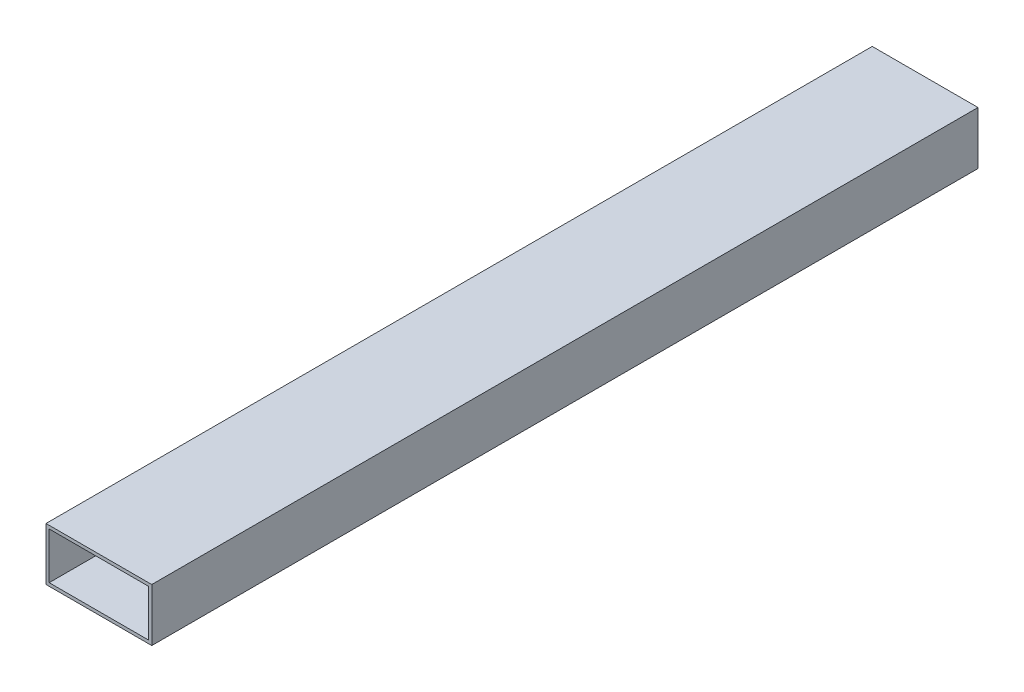
SolidWorks part; units mm, degrees
ref_plane "Front Plane" through (0, 0, 0) normal (0, 0, 1) x (1, 0, 0)
ref_plane "Top Plane" through (0, 0, 0) normal (0, 1, 0) x (1, 0, 0)
ref_plane "Right Plane" through (0, 0, 0) normal (1, 0, 0) x (0, 0, -1)
sketch "Sketch1" plane through (0, 0, 0) normal (0, 0, 1) x (1, 0, 0)
  line L1 (-81.2829, 22.6771) -> (-132.0829, 22.6771)
  line L2 (-81.2829, 22.6771) -> (-81.2829, 48.0771)
  line L3 (-81.2829, 48.0771) -> (-132.0829, 48.0771)
  line L4 (-132.0829, 22.6771) -> (-132.0829, 48.0771)
  dimension "D1" = 50.8
  dimension "D2" = 25.4
extrude "Extrude-Thin1" add sketch "Sketch1" along normal blind 396.875 thin
